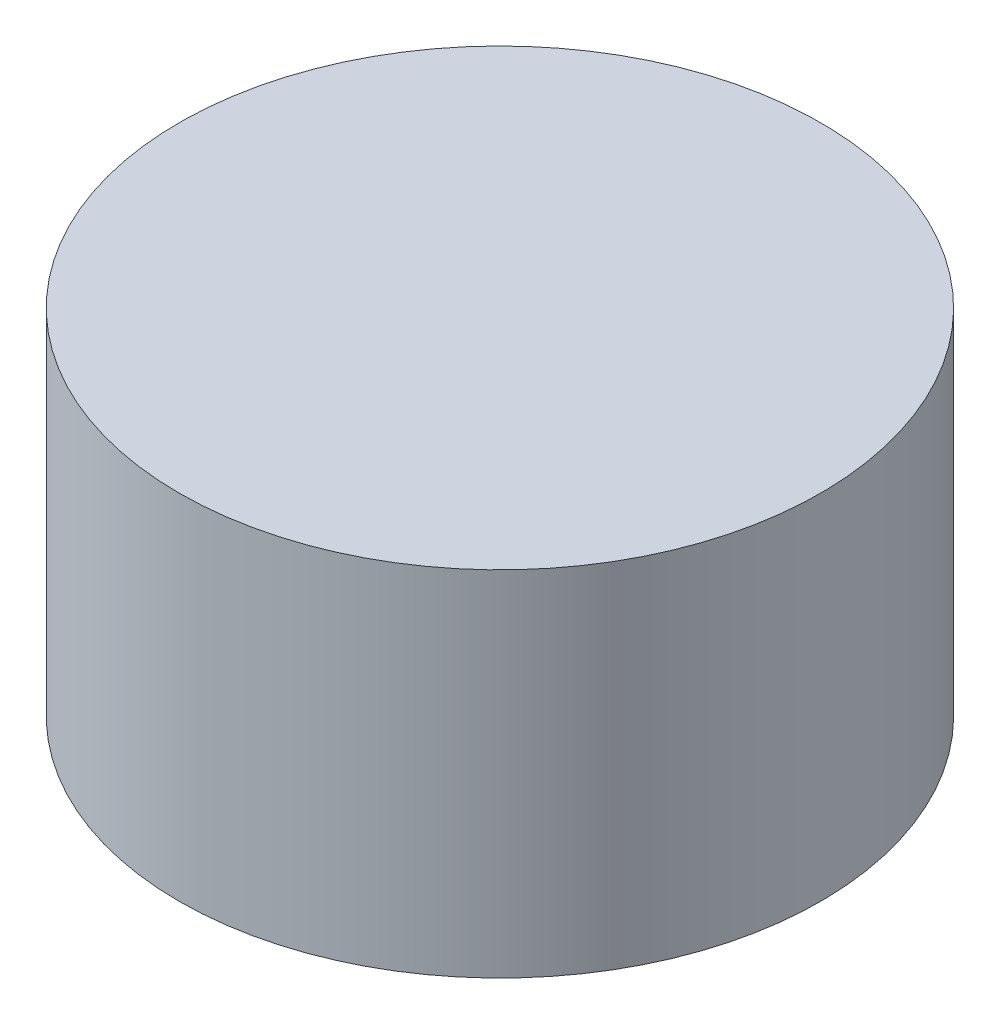
SolidWorks part; units mm, degrees
ref_plane "Front Plane" through (0, 0, 0) normal (0, 0, 1) x (1, 0, 0)
ref_plane "Top Plane" through (0, 0, 0) normal (0, 1, 0) x (1, 0, 0)
ref_plane "Right Plane" through (0, 0, 0) normal (1, 0, 0) x (0, 0, -1)
sketch "Sketch1" plane through (0, 0, 0) normal (0, 1, 0) x (1, 0, 0)
  circle A0 centre (0, 0) radius 31.115
  dimension "D1" = 62.23
extrude "Boss-Extrude1" add sketch "Sketch1" along normal blind 34.29
